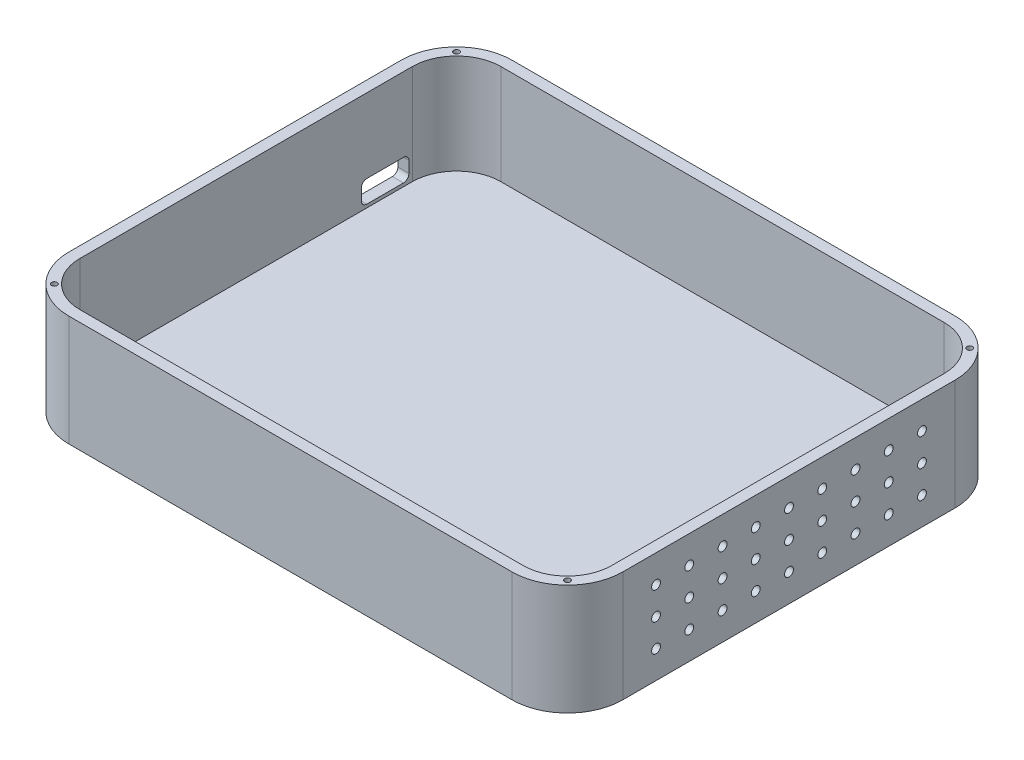
SolidWorks part; units mm, degrees
ref_plane "Front Plane" through (0, 0, 0) normal (0, 0, 1) x (1, 0, 0)
ref_plane "Top Plane" through (0, 0, 0) normal (0, 1, 0) x (1, 0, 0)
ref_plane "Right Plane" through (0, 0, 0) normal (1, 0, 0) x (0, 0, -1)
sketch "Sketch1" plane through (0, 0, 0) normal (0, 1, 0) x (1, 0, 0)
  line L1 (0, 0) -> (127, 0)
  line L2 (0, 0) -> (0, 101.6)
  line L3 (0, 101.6) -> (127, 101.6)
  line L4 (127, 0) -> (127, 101.6)
  dimension "D1" = 127
  dimension "D2" = 101.6
extrude "Boss-Extrude1" add sketch "Sketch1" along normal blind 2.54
sketch "Sketch2" plane through (0, 2.54, 0) normal (0, 1, 0) x (1, 0, 0)
  line L0 (0, 0) -> (127, 0) construction
  line L1 (127, 0) -> (127, 101.6) construction
  line L2 (127, 101.6) -> (0, 101.6) construction
  line L3 (0, 101.6) -> (0, 0) construction
  line L4 (0, 0) -> (127, 0)
  line L5 (127, 0) -> (127, 101.6)
  line L6 (127, 101.6) -> (0, 101.6)
  line L7 (0, 101.6) -> (0, 0)
  line L8 (124.46, 99.06) -> (2.54, 99.06)
  line L9 (2.54, 99.06) -> (2.54, 2.54)
  line L10 (2.54, 2.54) -> (124.46, 2.54)
  line L11 (124.46, 2.54) -> (124.46, 99.06)
  dimension "D1" = 2.54
extrude "Boss-Extrude2" add sketch "Sketch2" along normal blind 22.86
fillet "Fillet1" radius 10.16 4 edges at (124.46, 13.97, -99.06) (2.54, 13.97, -99.06) (2.54, 13.97, -2.54) (124.46, 13.97, -2.54)
fillet "Fillet2" radius 12.7 4 edges at (0, 12.7, -101.6) (127, 12.7, -101.6) (127, 12.7, 0) (0, 12.7, 0)
sketch "Sketch3" plane through (127, 0, 0) normal (1, 0, 0) x (0, 0, -1)
  line L0 (12.7, 12.7) -> (88.9, 12.7) construction
  line L1 (12.7, 25.4) -> (12.7, 0) construction
  line L2 (88.9, 0) -> (88.9, 25.4) construction
  line L3 (88.9, 12.7) -> (88.9, 19.05) construction
  line L4 (88.9, 19.05) -> (88.9, 5.3812) construction
  line L5 (50.8, 25.4) -> (50.8, 0) construction
  line L6 (12.7, 25.4) -> (88.9, 25.4) construction
  line L7 (12.7, 0) -> (88.9, 0) construction
  circle A0 centre (50.8, 12.7) radius 1.016
  circle A1 centre (58.42, 12.7) radius 1.016
  circle A2 centre (66.04, 12.7) radius 1.016
  circle A3 centre (73.66, 12.7) radius 1.016
  circle A4 centre (81.28, 12.7) radius 1.016
  circle A5 centre (43.18, 12.7) radius 1.016
  circle A6 centre (35.56, 12.7) radius 1.016
  circle A7 centre (27.94, 12.7) radius 1.016
  circle A8 centre (20.32, 12.7) radius 1.016
  circle A9 centre (20.32, 19.05) radius 1.016
  circle A10 centre (27.94, 19.05) radius 1.016
  circle A11 centre (35.56, 19.05) radius 1.016
  circle A12 centre (43.18, 19.05) radius 1.016
  circle A13 centre (50.8, 19.05) radius 1.016
  circle A14 centre (58.42, 19.05) radius 1.016
  circle A15 centre (66.04, 19.05) radius 1.016
  circle A16 centre (73.66, 19.05) radius 1.016
  circle A17 centre (81.28, 19.05) radius 1.016
  circle A18 centre (20.32, 6.35) radius 1.016
  circle A19 centre (27.94, 6.35) radius 1.016
  circle A20 centre (35.56, 6.35) radius 1.016
  circle A21 centre (43.18, 6.35) radius 1.016
  circle A22 centre (50.8, 6.35) radius 1.016
  circle A23 centre (58.42, 6.35) radius 1.016
  circle A24 centre (66.04, 6.35) radius 1.016
  circle A25 centre (73.66, 6.35) radius 1.016
  circle A26 centre (81.28, 6.35) radius 1.016
  dimension "D1" = 5
  dimension "D2" = 5
  dimension "D3" = 2
  dimension "D4" = 2
extrude "Cut-Extrude1" cut sketch "Sketch3" along direction (-1, 0, 0) on the side against the normal up to surface (2.54 mm away)
sketch "Sketch4" plane through (0, 0, 0) normal (-1, 0, 0) x (0, 0, 1)
  line L0 (-101.6, 3.302) -> (-88.138, 3.302)
  line L1 (-101.6, 0) -> (-101.6, 25.4) construction
  line L2 (-88.138, 3.302) -> (-88.138, 0)
  line L3 (-88.9, 0) -> (-12.7, 0) construction
  line L5 (-88.138, 3.302) -> (-77.216, 3.302)
  line L6 (-88.138, 3.302) -> (-88.138, 8.382)
  line L7 (-88.138, 8.382) -> (-77.216, 8.382)
  line L8 (-77.216, 3.302) -> (-77.216, 8.382)
  line M4 (-88.9, 25.4) -> (-88.9, 0)
extrude "Cut-Extrude2" cut sketch "Sketch4" along direction (1, 0, 0) on the side against the normal up to surface (2.54 mm away) contours L5 L8 L7 M4
fillet "Fillet3" radius 1.27 4 edges at (1.27, 3.302, -77.216) (1.27, 3.302, -88.138) (1.27, 8.382, -77.216) (1.27, 8.382, -88.138)
sketch "Sketch5" plane through (0, 0, -99.06) normal (0, 0, 1) x (1, 0, 0)
  line L1 (88.9, 21.0151) -> (97.9388, 21.0151)
  line L2 (88.9, 21.0151) -> (88.9, 15.6455)
  line L3 (88.9, 15.6455) -> (97.9388, 15.6455)
  line L4 (97.9388, 21.0151) -> (97.9388, 15.6455)
extrude "Cut-Extrude3" [suppressed] cut sketch "Sketch5" against normal through all
fillet "Fillet4" [suppressed] radius 1.27
sketch "Sketch6" plane through (0, 25.4, 0) normal (0, 1, 0) x (1, 0, 0)
  line L0 (0, 50.8) -> (127, 50.8) construction
  line L1 (0, 88.9) -> (0, 12.7) construction
  line L2 (127, 12.7) -> (127, 88.9) construction
  line L3 (63.5, 101.6) -> (63.5, 0) construction
  line L4 (114.3, 101.6) -> (12.7, 101.6) construction
  line L5 (12.7, 0) -> (114.3, 0) construction
  circle A0 centre (4.6818, 96.8913) radius 0.635
  circle A1 centre (4.6818, 4.7087) radius 0.635
  circle A2 centre (122.3182, 4.7087) radius 0.635
  circle A3 centre (122.3182, 96.8913) radius 0.635
extrude "Cut-Extrude4" cut sketch "Sketch6" against normal blind 7.62 contours A1 | A0 | A3 | A2
